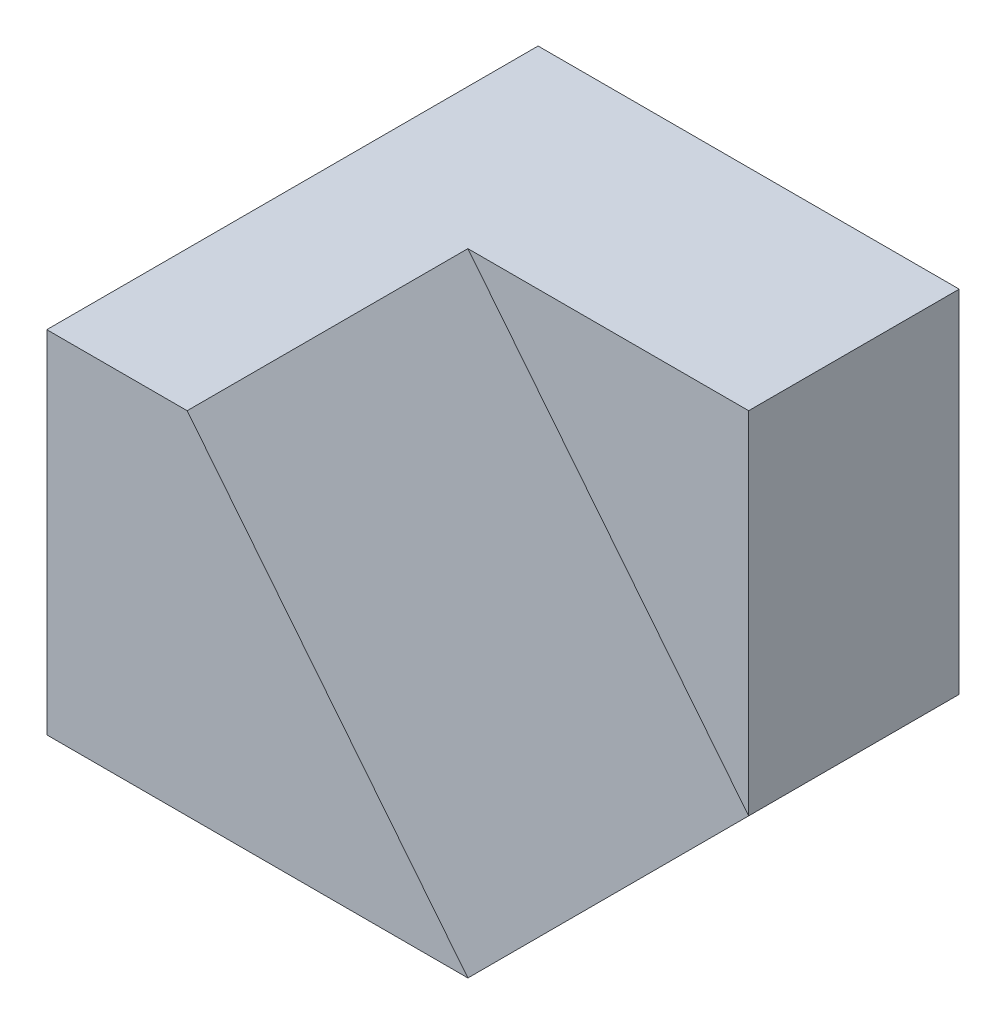
SolidWorks part; units mm, degrees
ref_plane "Plano frontal" through (0, 0, 0) normal (0, 0, 1) x (1, 0, 0)
ref_plane "Plano superior" through (0, 0, 0) normal (0, 1, 0) x (1, 0, 0)
ref_plane "Plano direito" through (0, 0, 0) normal (1, 0, 0) x (0, 0, -1)
sketch "Esboço1" plane through (0, 0, 0) normal (0, 0, 1) x (1, 0, 0)
  line L0 (0, 0) -> (60, 0)
  line L1 (0, 0) -> (0, 50)
  line L2 (0, 50) -> (20, 50)
  line L3 (20, 50) -> (60, 0)
  dimension "D1" = 60
  dimension "D2" = 50
  dimension "D3" = 20
extrude "Ressalto-extrusão1" add sketch "Esboço1" along normal blind 40
sketch "Esboço2" plane through (0, 0, 0) normal (0, 0, -1) x (-1, 0, 0)
  line L1 (-60, 0) -> (0, 0)
  line L2 (-60, 0) -> (-60, 50)
  line L3 (-60, 50) -> (0, 50)
  line L4 (0, 0) -> (0, 50)
extrude "Ressalto-extrusão2" add sketch "Esboço2" along normal blind 30
